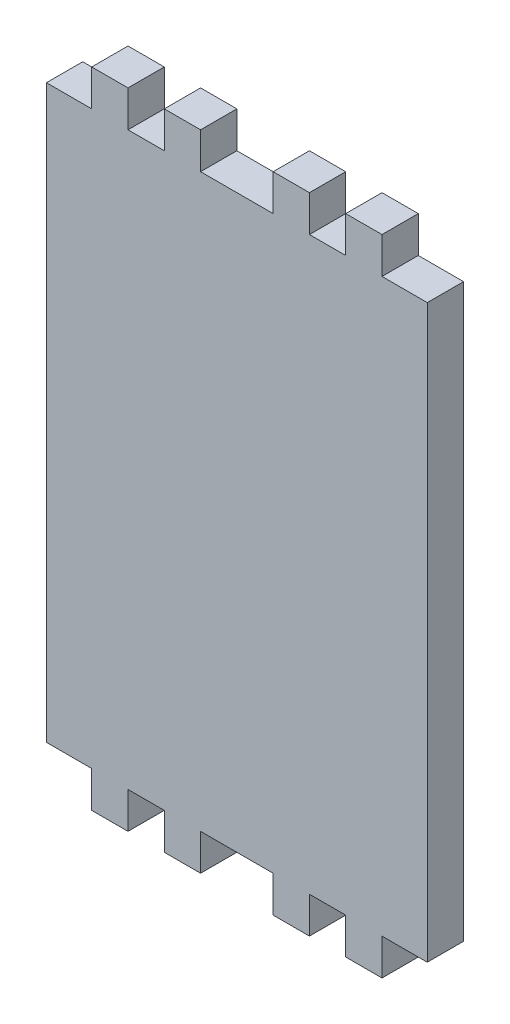
SolidWorks part; units mm, degrees
ref_plane "Front Plane" through (0, 0, 0) normal (0, 0, 1) x (1, 0, 0)
ref_plane "Top Plane" through (0, 0, 0) normal (0, 1, 0) x (1, 0, 0)
ref_plane "Right Plane" through (0, 0, 0) normal (1, 0, 0) x (0, 0, -1)
sketch "Sketch1" plane through (0, 0, 0) normal (0, 0, 1) x (1, 0, 0)
  line L1 (-6.9548, 43.3515) -> (46.3652, 43.3515)
  line L2 (-6.9548, 43.3515) -> (-6.9548, -36.6285)
  line L3 (-6.9548, -36.6285) -> (46.3652, -36.6285)
  line L4 (46.3652, 43.3515) -> (46.3652, -36.6285)
  dimension "D1" = 53.32
  dimension "D2" = 79.98
extrude "Boss-Extrude1" add sketch "Sketch1" along normal blind 5.08
sketch "Sketch2" plane through (0, 0, 5.08) normal (0, 0, 1) x (1, 0, 0)
  line L0 (19.7052, 43.3515) -> (19.7052, -36.6285) construction
  line L1 (46.3652, 43.3515) -> (-6.9548, 43.3515) construction
  line L2 (-6.9548, -36.6285) -> (46.3652, -36.6285) construction
  line L3 (-6.9548, 3.3615) -> (46.3652, 3.3615) construction
  line L4 (-6.9548, 43.3515) -> (-6.9548, -36.6285) construction
  line L5 (46.3652, -36.6285) -> (46.3652, 43.3515) construction
  line L6 (-0.6148, 43.3515) -> (-0.6148, 48.4315)
  line L7 (24.7852, 48.4315) -> (29.8652, 48.4315)
  line L8 (24.7852, 48.4315) -> (24.7852, 43.3515)
  line L9 (24.7852, 43.3515) -> (29.8652, 43.3515)
  line L10 (29.8652, 48.4315) -> (29.8652, 43.3515)
  line L11 (34.9452, 43.3515) -> (40.0252, 43.3515)
  line L12 (34.9452, 43.3515) -> (34.9452, 48.4315)
  line L13 (34.9452, 48.4315) -> (40.0252, 48.4315)
  line L14 (40.0252, 43.3515) -> (40.0252, 48.4315)
  line L15 (4.4652, 48.4315) -> (-0.6148, 48.4315)
  line L16 (4.4652, 43.3515) -> (4.4652, 48.4315)
  line L17 (4.4652, 43.3515) -> (-0.6148, 43.3515)
  line L18 (9.5452, 48.4315) -> (9.5452, 43.3515)
  line L19 (14.6252, 43.3515) -> (9.5452, 43.3515)
  line L20 (14.6252, 48.4315) -> (14.6252, 43.3515)
  line L21 (14.6252, 48.4315) -> (9.5452, 48.4315)
  line L22 (14.6252, -41.7085) -> (9.5452, -41.7085)
  line L23 (14.6252, -41.7085) -> (14.6252, -36.6285)
  line L24 (14.6252, -36.6285) -> (9.5452, -36.6285)
  line L25 (9.5452, -41.7085) -> (9.5452, -36.6285)
  line L26 (4.4652, -36.6285) -> (-0.6148, -36.6285)
  line L27 (4.4652, -36.6285) -> (4.4652, -41.7085)
  line L28 (4.4652, -41.7085) -> (-0.6148, -41.7085)
  line L29 (40.0252, -36.6285) -> (40.0252, -41.7085)
  line L30 (34.9452, -41.7085) -> (40.0252, -41.7085)
  line L31 (34.9452, -36.6285) -> (34.9452, -41.7085)
  line L32 (34.9452, -36.6285) -> (40.0252, -36.6285)
  line L33 (29.8652, -41.7085) -> (29.8652, -36.6285)
  line L34 (24.7852, -36.6285) -> (29.8652, -36.6285)
  line L35 (24.7852, -41.7085) -> (24.7852, -36.6285)
  line L36 (24.7852, -41.7085) -> (29.8652, -41.7085)
  line L37 (-0.6148, -36.6285) -> (-0.6148, -41.7085)
  dimension "D1" = 5.08
  dimension "D2" = 5.08
  dimension "D3" = 5.08
  dimension "D4" = 5.08
  dimension "D5" = 5.08
  dimension "D6" = 5.08
extrude "Boss-Extrude2" add sketch "Sketch2" against normal blind 5.08
sketch "Sketch3" plane through (0, 0, 5.08) normal (0, 0, 1) x (1, 0, 0)
  line L0 (-6.9548, 30.0215) -> (46.3652, 30.0215)
  line L1 (-6.9548, 43.3515) -> (-6.9548, -36.6285) construction
  line L2 (46.3652, -36.6285) -> (46.3652, 43.3515) construction
  line L3 (-6.9548, -23.2985) -> (46.3652, -23.2985)
  line L4 (46.3652, 43.3515) -> (40.0252, 43.3515) construction
  line L5 (40.0252, -36.6285) -> (46.3652, -36.6285) construction
  dimension "D1" = 13.33
  dimension "D2" = 13.33
